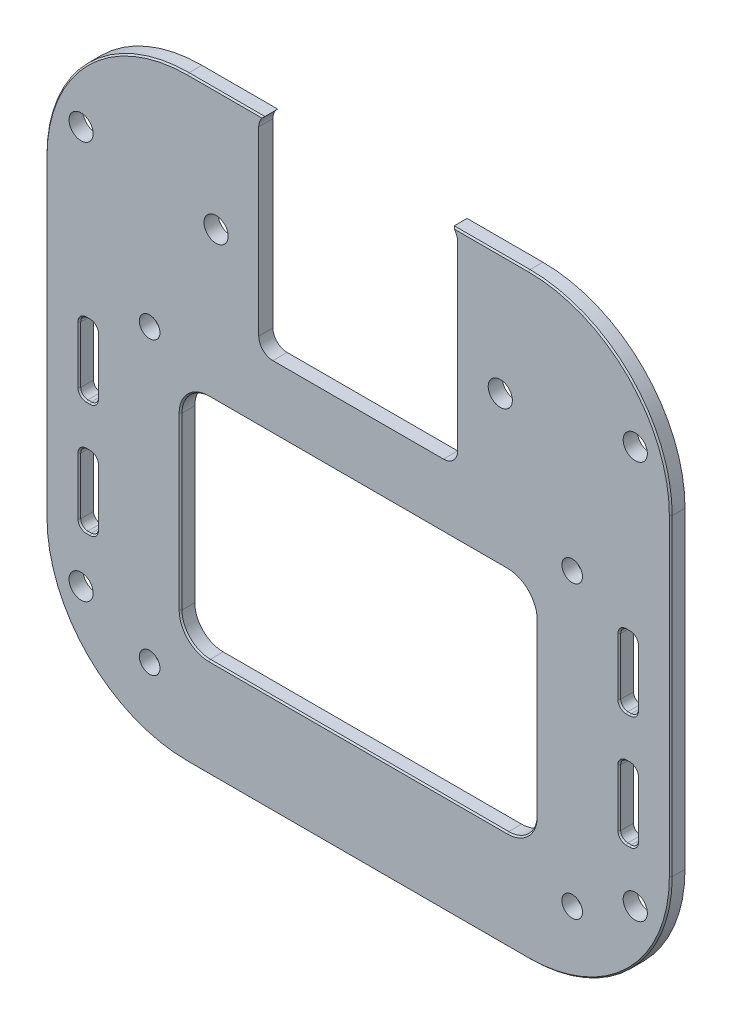
SolidWorks part; units mm, degrees
ref_plane "前视基准面" through (0, 0, 0) normal (0, 0, 1) x (1, 0, 0)
ref_plane "上视基准面" through (0, 0, 0) normal (0, 1, 0) x (1, 0, 0)
ref_plane "右视基准面" through (0, 0, 0) normal (1, 0, 0) x (0, 0, -1)
other "Configuration Table"
sketch "屏幕圆角承架_厂家孔轴与通风口" plane through (0, 0, 0) normal (0, 0, 1) x (1, 0, 0)
  line L0 (-24, -42) -> (24, -42)
  line L1 (44, -22) -> (44, 22)
  line L2 (24, 42) -> (-24, 42)
  line L3 (-44, 22) -> (-44, -22)
  line L4 (-21, -28) -> (21, -28)
  line L5 (25, -24) -> (25, 0)
  line L6 (21, 4) -> (-21, 4)
  line L7 (-25, 0) -> (-25, -24)
  arc A0 (24, -42) -> (44, -22) centre (24, -22) ccw
  arc A1 (44, 22) -> (24, 42) centre (24, 22) ccw
  arc A2 (-24, 42) -> (-44, 22) centre (-24, 22) ccw
  arc A3 (-44, -22) -> (-24, -42) centre (-24, -22) ccw
  arc A4 (21, -28) -> (25, -24) centre (21, -24) ccw
  arc A5 (25, 0) -> (21, 4) centre (21, 0) ccw
  arc A6 (-21, 4) -> (-25, 0) centre (-21, 0) ccw
  arc A7 (-25, -24) -> (-21, -28) centre (-21, -24) ccw
  circle A8 centre (-29.35, 8.45) radius 1.45
  circle A9 centre (-29.35, -32.45) radius 1.45
  circle A10 centre (30.12, 8.45) radius 1.45
  circle A11 centre (30.12, -32.45) radius 1.45
  circle A12 centre (-39, -28) radius 1.7
  circle A13 centre (-39, 28) radius 1.7
  circle A14 centre (39, -28) radius 1.7
  circle A15 centre (39, 28) radius 1.7
  dimension "D1" = 3.4
  dimension "D2" = 2.9
  dimension "D3" = 20
  dimension "D4" = 4
  dimension "D5" = 5
  dimension "D6" = 13.88
  dimension "D7" = 19
  dimension "D8" = 69
  dimension "D9" = 73.35
  dimension "D10" = 83
  dimension "D11" = 88
  dimension "D12" = 14
  dimension "D13" = 33.55
  dimension "D14" = 38
  dimension "D15" = 70
  dimension "D16" = 74.45
  dimension "D17" = 84
extrude "屏幕承架厚2" add sketch "屏幕圆角承架_厂家孔轴与通风口" along normal blind 2
sketch "摄像板可换安装区26乘25" plane through (0, 0, 0) normal (0, 0, 1) x (1, 0, 0)
  line L0 (-11, 17.5) -> (11, 17.5)
  line L1 (13, 19.5) -> (13, 40.5)
  line L2 (11, 42.5) -> (-11, 42.5)
  line L3 (-13, 40.5) -> (-13, 19.5)
  arc A0 (11, 17.5) -> (13, 19.5) centre (11, 19.5) ccw
  arc A1 (13, 40.5) -> (11, 42.5) centre (11, 40.5) ccw
  arc A2 (-11, 42.5) -> (-13, 40.5) centre (-11, 40.5) ccw
  arc A3 (-13, 19.5) -> (-11, 17.5) centre (-11, 19.5) ccw
  dimension "D1" = 2
  dimension "D2" = 26
  dimension "D3" = 25
extrude "摄像板安装区避空" cut sketch "摄像板可换安装区26乘25" along normal through all
sketch "四处隐藏扎带应力释放槽" plane through (0, 0, 0) normal (0, 0, 1) x (1, 0, 0)
  line L0 (-38.25, -21) -> (-37.75, -21)
  line L1 (-36.75, -20) -> (-36.75, -12)
  line L2 (-37.75, -11) -> (-38.25, -11)
  line L3 (-39.25, -12) -> (-39.25, -20)
  line L4 (-38.25, -5) -> (-37.75, -5)
  line L5 (-36.75, -4) -> (-36.75, 4)
  line L6 (-37.75, 5) -> (-38.25, 5)
  line L7 (-39.25, 4) -> (-39.25, -4)
  line L8 (37.75, -21) -> (38.25, -21)
  line L9 (39.25, -20) -> (39.25, -12)
  line L10 (38.25, -11) -> (37.75, -11)
  line L11 (36.75, -12) -> (36.75, -20)
  line L12 (37.75, -5) -> (38.25, -5)
  line L13 (39.25, -4) -> (39.25, 4)
  line L14 (38.25, 5) -> (37.75, 5)
  line L15 (36.75, 4) -> (36.75, -4)
  arc A0 (-37.75, -21) -> (-36.75, -20) centre (-37.75, -20) ccw
  arc A1 (-36.75, -12) -> (-37.75, -11) centre (-37.75, -12) ccw
  arc A2 (-38.25, -11) -> (-39.25, -12) centre (-38.25, -12) ccw
  arc A3 (-39.25, -20) -> (-38.25, -21) centre (-38.25, -20) ccw
  arc A4 (-37.75, -5) -> (-36.75, -4) centre (-37.75, -4) ccw
  arc A5 (-36.75, 4) -> (-37.75, 5) centre (-37.75, 4) ccw
  arc A6 (-38.25, 5) -> (-39.25, 4) centre (-38.25, 4) ccw
  arc A7 (-39.25, -4) -> (-38.25, -5) centre (-38.25, -4) ccw
  arc A8 (38.25, -21) -> (39.25, -20) centre (38.25, -20) ccw
  arc A9 (39.25, -12) -> (38.25, -11) centre (38.25, -12) ccw
  arc A10 (37.75, -11) -> (36.75, -12) centre (37.75, -12) ccw
  arc A11 (36.75, -20) -> (37.75, -21) centre (37.75, -20) ccw
  arc A12 (38.25, -5) -> (39.25, -4) centre (38.25, -4) ccw
  arc A13 (39.25, 4) -> (38.25, 5) centre (38.25, 4) ccw
  arc A14 (37.75, 5) -> (36.75, 4) centre (37.75, 4) ccw
  arc A15 (36.75, -4) -> (37.75, -5) centre (37.75, -4) ccw
  dimension "D1" = 1
  dimension "D2" = 2.5
  dimension "D3" = 76
  dimension "D4" = 10
  dimension "D5" = 16
extrude "内侧走线扎带槽贯穿" cut sketch "四处隐藏扎带应力释放槽" along normal through all
chamfer "非功能外缘倒角_C0.2" distance 0.2 angle 45 56 edges at (36.75, 0, 2) (37.0429, 4.7071, 2) (38, 5, 2) (38.9571, 4.7071, 2) (39.25, 0, 2) (38.9571, -4.7071, 2) (38, -5, 2) (37.0429, -4.7071, 2) (36.75, -16, 2) (37.0429, -11.2929, 2) (38, -11, 2) (38.9571, -11.2929, 2) (39.25, -16, 2) (38.9571, -20.7071, 2) (38, -21, 2) (37.0429, -20.7071, 2) (-39.25, 0, 2) (-38.9571, 4.7071, 2) (-38, 5, 2) (-37.0429, 4.7071, 2) (-36.75, 0, 2) (-37.0429, -4.7071, 2) (-38, -5, 2) (-38.9571, -4.7071, 2) (-38.9571, -20.7071, 2) (-38, -21, 2) (-37.0429, -20.7071, 2) (-36.75, -16, 2) (-37.0429, -11.2929, 2) (-38, -11, 2) (-38.9571, -11.2929, 2) (-39.25, -16, 2) (-23.8284, -26.8284, 2) (0, -28, 2) (23.8284, -26.8284, 2) (25, -12, 2) (23.8284, 2.8284, 2) (0, 4, 2) (-23.8284, 2.8284, 2) (-25, -12, 2) (-12.4142, 18.0858, 2) (0, 17.5, 2) (12.4142, 18.0858, 2) (13, 30, 2) (12.8229, 41.3229, 2) (-13, 30, 2) (-12.8229, 41.3229, 2) (18.1614, 42, 2) (38.1421, 36.1421, 2) (44, 0, 2) (38.1421, -36.1421, 2) (0, -42, 2) (-38.1421, -36.1421, 2) (-18.1614, 42, 2) (-38.1421, 36.1421, 2) (-44, 0, 2)
sketch "相机螺母与后插座避空28乘29_5" plane through (0, 0, 0) normal (0, 0, 1) x (1, 0, 0)
  line L0 (-12, 13) -> (12, 13)
  line L1 (14, 15) -> (14, 40.5)
  line L2 (12, 42.5) -> (-12, 42.5)
  line L3 (-14, 40.5) -> (-14, 15)
  arc A0 (12, 13) -> (14, 15) centre (12, 15) ccw
  arc A1 (14, 40.5) -> (12, 42.5) centre (12, 40.5) ccw
  arc A2 (-12, 42.5) -> (-14, 40.5) centre (-12, 40.5) ccw
  arc A3 (-14, 15) -> (-12, 13) centre (-12, 15) ccw
  dimension "D1" = 2
  dimension "D2" = 28
  dimension "D3" = 29.5
extrude "可换相机托架下部维修避空" cut sketch "相机螺母与后插座避空28乘29_5" along normal through all
sketch "相机托架双M3连接孔" plane through (0, 0, 0) normal (0, 0, 1) x (1, 0, 0)
  circle A0 centre (-20, 25) radius 1.7
  circle A1 centre (20, 25) radius 1.7
  dimension "D1" = 3.4
  dimension "D2" = 40
extrude "托架安装孔贯通" cut sketch "相机托架双M3连接孔" along normal through all
